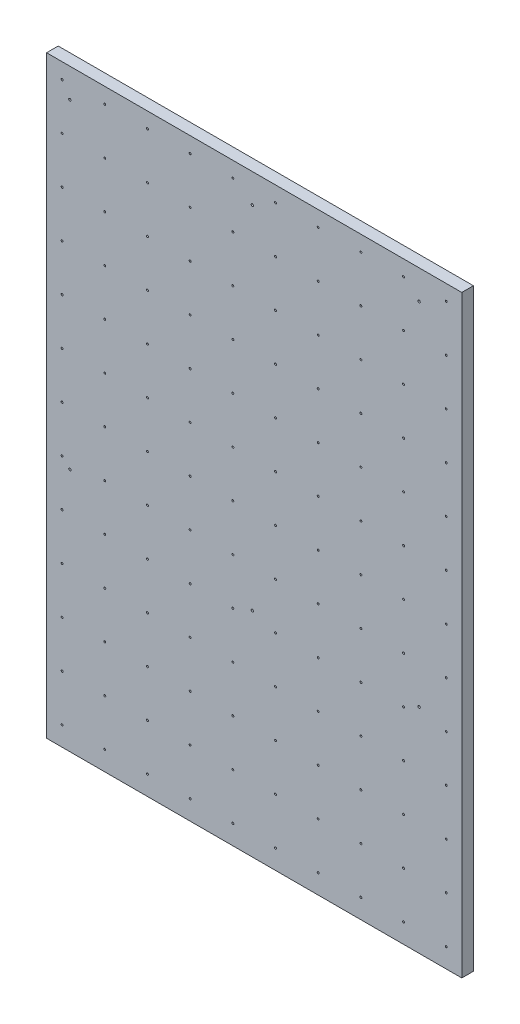
SolidWorks part; units mm, degrees
material "Фанера, берёза, ФСФ ВВ/С ГОСТ 3916.1-96"
ref_plane "Спереди" through (0, 0, 0) normal (0, 0, 1) x (1, 0, 0)
ref_plane "Сверху" through (0, 0, 0) normal (0, 1, 0) x (1, 0, 0)
ref_plane "Справа" through (0, 0, 0) normal (1, 0, 0) x (0, 0, -1)
sketch "Эскиз1" plane through (0, 0, 0) normal (0, 0, 1) x (1, 0, 0)
  line L1 (-535, 765) -> (535, 765)
  line L2 (-535, 765) -> (-535, -765)
  line L3 (-535, -765) -> (535, -765)
  line L4 (535, 765) -> (535, -765)
  line L5 (0, -765) -> (0, 765) construction
  line L6 (-535, 0) -> (535, 0) construction
  point P0 (0, 0)
  dimension "D1" = 1070
  dimension "D2" = 1530
extrude "Бобышка-Вытянуть1" add sketch "Эскиз1" along normal mid plane 30
sketch "Эскиз2" plane through (0, 0, 15) normal (0, 0, 1) x (1, 0, 0)
  line L0 (-535, 765) -> (-535, -765) construction
  line L1 (535, 765) -> (-535, 765) construction
  line L2 (-495, 725) -> (-385, 725) construction
  circle A0 centre (-495, 725) radius 2.5
  circle A1 centre (-385, 725) radius 2.5
  circle A2 centre (-275, 725) radius 2.5
  circle A3 centre (-165, 725) radius 2.5
  circle A4 centre (-55, 725) radius 2.5
  circle A5 centre (55, 725) radius 2.5
  circle A6 centre (165, 725) radius 2.5
  circle A7 centre (275, 725) radius 2.5
  circle A8 centre (385, 725) radius 2.5
  circle A9 centre (495, 725) radius 2.5
  circle A10 centre (-385, 605) radius 2.5
  circle A11 centre (-275, 605) radius 2.5
  circle A12 centre (-165, 605) radius 2.5
  circle A13 centre (-55, 605) radius 2.5
  circle A14 centre (55, 605) radius 2.5
  circle A15 centre (165, 605) radius 2.5
  circle A16 centre (275, 605) radius 2.5
  circle A17 centre (385, 605) radius 2.5
  circle A18 centre (495, 605) radius 2.5
  circle A19 centre (-385, 485) radius 2.5
  circle A20 centre (-275, 485) radius 2.5
  circle A21 centre (-165, 485) radius 2.5
  circle A22 centre (-55, 485) radius 2.5
  circle A23 centre (55, 485) radius 2.5
  circle A24 centre (165, 485) radius 2.5
  circle A25 centre (275, 485) radius 2.5
  circle A26 centre (385, 485) radius 2.5
  circle A27 centre (495, 485) radius 2.5
  circle A28 centre (-385, 365) radius 2.5
  circle A29 centre (-275, 365) radius 2.5
  circle A30 centre (-165, 365) radius 2.5
  circle A31 centre (-55, 365) radius 2.5
  circle A32 centre (55, 365) radius 2.5
  circle A33 centre (165, 365) radius 2.5
  circle A34 centre (275, 365) radius 2.5
  circle A35 centre (385, 365) radius 2.5
  circle A36 centre (495, 365) radius 2.5
  circle A37 centre (-385, 245) radius 2.5
  circle A38 centre (-275, 245) radius 2.5
  circle A39 centre (-165, 245) radius 2.5
  circle A40 centre (-55, 245) radius 2.5
  circle A41 centre (55, 245) radius 2.5
  circle A42 centre (165, 245) radius 2.5
  circle A43 centre (275, 245) radius 2.5
  circle A44 centre (385, 245) radius 2.5
  circle A45 centre (495, 245) radius 2.5
  circle A46 centre (-385, 125) radius 2.5
  circle A47 centre (-275, 125) radius 2.5
  circle A48 centre (-165, 125) radius 2.5
  circle A49 centre (-55, 125) radius 2.5
  circle A50 centre (55, 125) radius 2.5
  circle A51 centre (165, 125) radius 2.5
  circle A52 centre (275, 125) radius 2.5
  circle A53 centre (385, 125) radius 2.5
  circle A54 centre (495, 125) radius 2.5
  circle A55 centre (-385, 5) radius 2.5
  circle A56 centre (-275, 5) radius 2.5
  circle A57 centre (-165, 5) radius 2.5
  circle A58 centre (-55, 5) radius 2.5
  circle A59 centre (55, 5) radius 2.5
  circle A60 centre (165, 5) radius 2.5
  circle A61 centre (275, 5) radius 2.5
  circle A62 centre (385, 5) radius 2.5
  circle A63 centre (495, 5) radius 2.5
  circle A64 centre (-385, -115) radius 2.5
  circle A65 centre (-275, -115) radius 2.5
  circle A66 centre (-165, -115) radius 2.5
  circle A67 centre (-55, -115) radius 2.5
  circle A68 centre (55, -115) radius 2.5
  circle A69 centre (165, -115) radius 2.5
  circle A70 centre (275, -115) radius 2.5
  circle A71 centre (385, -115) radius 2.5
  circle A72 centre (495, -115) radius 2.5
  circle A73 centre (-385, -235) radius 2.5
  circle A74 centre (-275, -235) radius 2.5
  circle A75 centre (-165, -235) radius 2.5
  circle A76 centre (-55, -235) radius 2.5
  circle A77 centre (55, -235) radius 2.5
  circle A78 centre (165, -235) radius 2.5
  circle A79 centre (275, -235) radius 2.5
  circle A80 centre (385, -235) radius 2.5
  circle A81 centre (495, -235) radius 2.5
  circle A82 centre (-385, -355) radius 2.5
  circle A83 centre (-275, -355) radius 2.5
  circle A84 centre (-165, -355) radius 2.5
  circle A85 centre (-55, -355) radius 2.5
  circle A86 centre (55, -355) radius 2.5
  circle A87 centre (165, -355) radius 2.5
  circle A88 centre (275, -355) radius 2.5
  circle A89 centre (385, -355) radius 2.5
  circle A90 centre (495, -355) radius 2.5
  circle A91 centre (-385, -475) radius 2.5
  circle A92 centre (-275, -475) radius 2.5
  circle A93 centre (-165, -475) radius 2.5
  circle A94 centre (-55, -475) radius 2.5
  circle A95 centre (55, -475) radius 2.5
  circle A96 centre (165, -475) radius 2.5
  circle A97 centre (275, -475) radius 2.5
  circle A98 centre (385, -475) radius 2.5
  circle A99 centre (495, -475) radius 2.5
  circle A100 centre (-385, -595) radius 2.5
  circle A101 centre (-275, -595) radius 2.5
  circle A102 centre (-165, -595) radius 2.5
  circle A103 centre (-55, -595) radius 2.5
  circle A104 centre (55, -595) radius 2.5
  circle A105 centre (165, -595) radius 2.5
  circle A106 centre (275, -595) radius 2.5
  circle A107 centre (385, -595) radius 2.5
  circle A108 centre (495, -595) radius 2.5
  circle A109 centre (-385, -715) radius 2.5
  circle A110 centre (-275, -715) radius 2.5
  circle A111 centre (-165, -715) radius 2.5
  circle A112 centre (-55, -715) radius 2.5
  circle A113 centre (55, -715) radius 2.5
  circle A114 centre (165, -715) radius 2.5
  circle A115 centre (275, -715) radius 2.5
  circle A116 centre (385, -715) radius 2.5
  circle A117 centre (495, -715) radius 2.5
  circle A118 centre (-495, 605) radius 2.5
  circle A119 centre (-495, 485) radius 2.5
  circle A120 centre (-495, 365) radius 2.5
  circle A121 centre (-495, 245) radius 2.5
  circle A122 centre (-495, 125) radius 2.5
  circle A123 centre (-495, 5) radius 2.5
  circle A124 centre (-495, -115) radius 2.5
  circle A125 centre (-495, -235) radius 2.5
  circle A126 centre (-495, -355) radius 2.5
  circle A127 centre (-495, -475) radius 2.5
  circle A128 centre (-495, -595) radius 2.5
  circle A129 centre (-495, -715) radius 2.5
  dimension "D1" = 5
  dimension "D2" = 40
  dimension "D3" = 40
  dimension "D6" = 110
  dimension "D4" = 10
  dimension "D5" = 13
extrude "Вырез-Вытянуть1" cut sketch "Эскиз2" against normal through all
sketch "Эскиз3" plane through (0, 0, 15) normal (0, 0, 1) x (1, 0, 0)
  circle A0 centre (-475, 690) radius 3 construction
  circle A1 centre (-5, 690) radius 3 construction
  circle A2 centre (425, 690) radius 3 construction
  circle A3 centre (-475, -135) radius 3 construction
  circle A4 centre (-5, -215) radius 3 construction
  circle A5 centre (425, -215) radius 3 construction
  circle A6 centre (-475, 690) radius 3
  circle A7 centre (-5, 690) radius 3
  circle A8 centre (425, 690) radius 3
  circle A9 centre (-475, -135) radius 3
  circle A10 centre (-5, -215) radius 3
  circle A11 centre (425, -215) radius 3
extrude "Вырез-Вытянуть2" cut sketch "Эскиз3" against normal through all
equation "\"ширина 1-я панель\"=1145"
equation "\"толщина дсп\"=30"
equation "\"D1@Эскиз1\"=\"ширина 2-я панель\""
equation "\"D3@Эскиз2\"=\"D2@Эскиз2\""
equation "\"длина панелей\"=1530"
equation "\"ширина 2-я панель\"=1070"
equation "\"D2@Эскиз1\"=\"длина панелей\""
